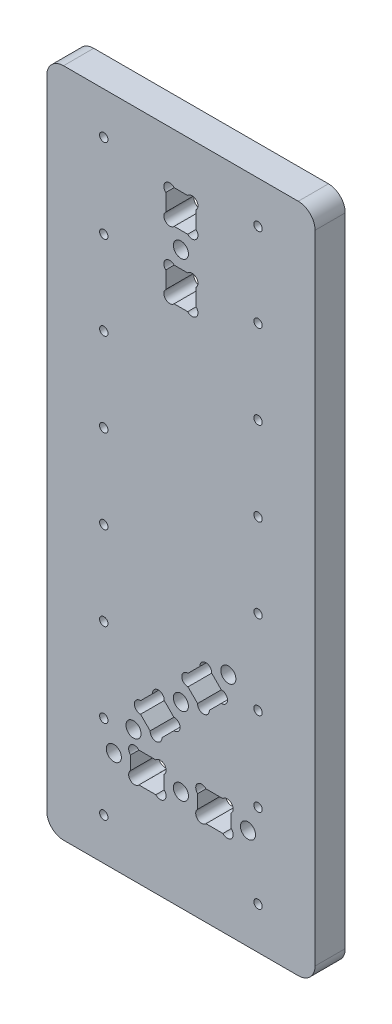
SolidWorks part; units mm, degrees
ref_plane "Plan de face" through (0, 0, 0) normal (0, 0, 1) x (1, 0, 0)
ref_plane "Plan de dessus" through (0, 0, 0) normal (0, 1, 0) x (1, 0, 0)
ref_plane "Plan de droite" through (0, 0, 0) normal (1, 0, 0) x (0, 0, -1)
sketch "Esquisse1" plane through (0, 0, 0) normal (0, 0, 1) x (1, 0, 0)
  line L1 (0, 0) -> (80, 0)
  line L2 (0, 0) -> (0, 200)
  line L3 (0, 200) -> (80, 200)
  line L4 (80, 0) -> (80, 200)
  dimension "D1" = 80
  dimension "D2" = 200
extrude "Boss.-Extru.1" add sketch "Esquisse1" along normal blind 9
sketch "Esquisse2" plane through (0, 0, 9) normal (0, 0, 1) x (1, 0, 0)
  line L0 (40, 0) -> (40, 200) construction
  line L1 (0, 0) -> (80, 0) construction
  line L2 (80, 200) -> (0, 200) construction
  line L3 (17, 0) -> (17, 200) construction
  line L4 (40, 100) -> (0, 100) construction
  line L5 (0, 200) -> (0, 0) construction
  circle A0 centre (17, 187.5) radius 1.25
  circle A1 centre (17, 87.5) radius 1.25
  circle A2 centre (17, 62.5) radius 1.25
  circle A3 centre (17, 37.5) radius 1.25
  circle A4 centre (17, 12.5) radius 1.25
  circle A5 centre (17, 162.5) radius 1.25
  circle A6 centre (17, 137.5) radius 1.25
  circle A7 centre (17, 112.5) radius 1.25
  circle A8 centre (63, 112.5) radius 1.25
  circle A9 centre (63, 137.5) radius 1.25
  circle A10 centre (63, 162.5) radius 1.25
  circle A11 centre (63, 12.5) radius 1.25
  circle A12 centre (63, 37.5) radius 1.25
  circle A13 centre (63, 62.5) radius 1.25
  circle A14 centre (63, 87.5) radius 1.25
  circle A15 centre (63, 187.5) radius 1.25
  dimension "D2" = 2.5
  dimension "D3" = 12.5
  dimension "D4" = 25
  dimension "D5" = 25
  dimension "D1" = 23
  dimension "D6" = 25
extrude "Enlèv. mat.-Extru.1" cut sketch "Esquisse2" against normal through all both and the other way through all
sketch "Esquisse3" plane through (0, 0, 9) normal (0, 0, 1) x (1, 0, 0)
  line L0 (43.182, 0) -> (43.182, 50) construction
  line L2 (43.182, 50) -> (46.7175, 53.5355) construction
  line L3 (46.7175, 53.5355) -> (53.7886, 60.6066)
  line L4 (53.7886, 60.6066) -> (47.4246, 66.9706)
  line L5 (47.4246, 66.9706) -> (40.3536, 59.8995)
  line L6 (40.3536, 59.8995) -> (46.7175, 53.5355)
  line L7 (43.182, 50) -> (32.8481, 60.3339) construction
  line L8 (33.2825, 52.8284) -> (39.6464, 46.4645)
  line L9 (26.2114, 45.7574) -> (33.2825, 52.8284)
  line L10 (32.5754, 39.3934) -> (26.2114, 45.7574)
  line L11 (39.6464, 46.4645) -> (32.5754, 39.3934)
  line L12 (26.2114, 45.7574) -> (17, 45.7574) construction
  line L13 (17, 45.7574) -> (17, 37.5) construction
  line L14 (53.7886, 60.6066) -> (63, 60.6066) construction
  line L15 (63, 60.6066) -> (63, 37.5) construction
  line L16 (0, 0) -> (80, 0) construction
  dimension "D1" = 135
  dimension "D2" = 9
  dimension "D3" = 10
  dimension "D4" = 5
  dimension "D5" = 50
extrude "Enlèv. mat.-Extru.2" cut sketch "Esquisse3" against normal through all both and the other way through all
fillet "Congé1" radius 5 4 edges at (0, 200, 4.5) (80, 200, 4.5) (80, 0, 4.5) (0, 0, 4.5)
sketch "Esquisse4" plane through (0, 0, 9) normal (0, 0, 1) x (1, 0, 0)
  line L0 (32.5754, 39.3934) -> (26.2114, 45.7574) construction
  line L1 (26.2114, 45.7574) -> (33.2825, 52.8284) construction
  line L2 (27.8641, 45.7574) -> (26.2114, 45.7574) construction
  line L3 (27.9614, 47.5074) -> (27.9614, 44.0074)
  line L4 (26.2114, 45.7574) -> (26.1114, 45.7574) construction
  line L5 (29.3934, 42.5754) -> (36.4645, 49.6464) construction
  line L6 (33.2825, 52.8284) -> (39.6464, 46.4645) construction
  line L7 (29.747, 49.2929) -> (36.1109, 42.9289) construction
  line L8 (39.6464, 46.4645) -> (32.5754, 39.3934) construction
  line L9 (33.2825, 52.8284) -> (33.2825, 52.9284) construction
  line L10 (33.2825, 51.1757) -> (33.2825, 52.8284) construction
  line L11 (31.5325, 51.0784) -> (35.0325, 51.0784)
  line L12 (37.9937, 46.4645) -> (39.6464, 46.4645) construction
  line L13 (39.6464, 46.4645) -> (39.7464, 46.4645) construction
  line L14 (32.5754, 39.3934) -> (32.5754, 39.2934) construction
  line L15 (32.5754, 41.0461) -> (32.5754, 39.3934) construction
  line L16 (37.8964, 44.7145) -> (37.8964, 48.2145)
  line L17 (34.3254, 41.1434) -> (30.8254, 41.1434)
  line L18 (36.4645, 49.6464) -> (43.5355, 56.7175) construction
  line L19 (46.7175, 53.5355) -> (40.3536, 59.8995) construction
  line L20 (40, 53.182) -> (41.6519, 51.5301) construction
  line L21 (52.1359, 60.6066) -> (53.7886, 60.6066) construction
  line L22 (53.7886, 60.6066) -> (53.8886, 60.6066) construction
  line L23 (46.7175, 53.5355) -> (46.7175, 53.4355) construction
  line L24 (46.7175, 55.1882) -> (46.7175, 53.5355) construction
  line L25 (42.0063, 59.8995) -> (40.3536, 59.8995) construction
  line L26 (40.3536, 59.8995) -> (40.2536, 59.8995) construction
  line L27 (43.8891, 63.435) -> (50.253, 57.0711) construction
  line L28 (50.6066, 63.7886) -> (43.5355, 56.7175) construction
  line L29 (47.4246, 66.9706) -> (47.4246, 67.0706) construction
  line L30 (47.4246, 65.3179) -> (47.4246, 66.9706) construction
  line L31 (52.0386, 58.8566) -> (52.0386, 62.3566)
  line L32 (48.4675, 55.2855) -> (44.9675, 55.2855)
  line L33 (42.1036, 61.6495) -> (42.1036, 58.1495)
  line L34 (45.6746, 65.2206) -> (49.1746, 65.2206)
  line L35 (29.3934, 42.5754) -> (25.8579, 39.0398) construction
  arc A0 (27.9614, 44.0074) -> (27.9614, 47.5074) centre (27.8641, 45.7574) cw
  arc A1 (35.0325, 51.0784) -> (31.5325, 51.0784) centre (33.2825, 51.1757) ccw
  arc A2 (37.8964, 48.2145) -> (37.8964, 44.7145) centre (37.9937, 46.4645) cw
  arc A3 (30.8254, 41.1434) -> (34.3254, 41.1434) centre (32.5754, 41.0461) ccw
  arc A4 (52.0386, 62.3566) -> (52.0386, 58.8566) centre (52.1359, 60.6066) cw
  arc A5 (44.9675, 55.2855) -> (48.4675, 55.2855) centre (46.7175, 55.1882) ccw
  arc A6 (42.1036, 58.1495) -> (42.1036, 61.6495) centre (42.0063, 59.8995) cw
  arc A7 (49.1746, 65.2206) -> (45.6746, 65.2206) centre (47.4246, 65.3179) ccw
  circle A8 centre (40, 53.182) radius 2.25
  circle A9 centre (25.8579, 39.0398) radius 2.25
  circle A10 centre (54.1421, 67.3241) radius 2.25
  dimension "D2" = 3.5
  dimension "D3" = 5
  dimension "D4" = 4.5
  dimension "D1" = 0.1
extrude "Enlèv. mat.-Extru.3" cut sketch "Esquisse4" against normal through all both and the other way through all
sketch "Esquisse5" plane through (0, 0, 9) normal (0, 0, 1) x (1, 0, 0)
  line L0 (52.0386, 58.8566) -> (48.4675, 55.2855) construction
  line L1 (49.1746, 65.2206) -> (52.0386, 62.3566) construction
  line L2 (42.1036, 61.6495) -> (45.6746, 65.2206) construction
  line L3 (44.9675, 55.2855) -> (42.1036, 58.1495) construction
  line L4 (37.8964, 44.7145) -> (34.3254, 41.1434) construction
  line L5 (35.0325, 51.0784) -> (37.8964, 48.2145) construction
  line L6 (27.9614, 47.5074) -> (31.5325, 51.0784) construction
  line L7 (30.8254, 41.1434) -> (27.9614, 44.0074) construction
  line L8 (52.0386, 58.8566) -> (48.4675, 55.2855) construction
  line L9 (49.1746, 65.2206) -> (52.0386, 62.3566) construction
  line L10 (42.1036, 61.6495) -> (45.6746, 65.2206) construction
  line L11 (44.9675, 55.2855) -> (42.1036, 58.1495) construction
  line L12 (37.8964, 44.7145) -> (34.3254, 41.1434) construction
  line L13 (35.0325, 51.0784) -> (37.8964, 48.2145) construction
  line L14 (27.9614, 47.5074) -> (31.5325, 51.0784) construction
  line L15 (30.8254, 41.1434) -> (27.9614, 44.0074) construction
  line L16 (54.1421, 67.3241) -> (40, 53.182) construction
  line L17 (54.1421, 67.3241) -> (12.0169, 41.591) construction
  line L18 (52.5251, 25.5) -> (47.4749, 25.5)
  line L19 (55, 32.0251) -> (55, 27.9749)
  line L20 (47.4749, 34.5) -> (52.5251, 34.5)
  line L21 (45, 27.9749) -> (45, 32.0251)
  line L22 (32.5251, 25.5) -> (27.4749, 25.5)
  line L23 (35, 32.0251) -> (35, 27.9749)
  line L24 (27.4749, 34.5) -> (32.5251, 34.5)
  line L25 (25, 27.9749) -> (25, 32.0251)
  line L26 (60, 30) -> (40, 30) construction
  line L27 (40, 30) -> (40, 0) construction
  line L28 (44.5, 182.5251) -> (44.5, 177.4749)
  line L29 (5, 0) -> (75, 0) construction
  line L30 (37.9749, 185) -> (42.0251, 185)
  line L31 (35.5, 177.4749) -> (35.5, 182.5251)
  line L32 (42.0251, 175) -> (37.9749, 175)
  line L33 (44.5, 162.5251) -> (44.5, 157.4749)
  line L34 (37.9749, 165) -> (42.0251, 165)
  line L35 (35.5, 157.4749) -> (35.5, 162.5251)
  line L36 (42.0251, 155) -> (37.9749, 155)
  line L37 (40, 190) -> (40, 170) construction
  line L38 (75, 200) -> (5, 200) construction
  circle A0 centre (54.1421, 67.3241) radius 2.25 construction
  arc A1 (52.0386, 58.8566) -> (52.0386, 62.3566) centre (52.1359, 60.6066) ccw construction
  arc A2 (49.1746, 65.2206) -> (45.6746, 65.2206) centre (47.4246, 65.3179) ccw construction
  arc A3 (42.1036, 61.6495) -> (42.1036, 58.1495) centre (42.0063, 59.8995) ccw construction
  arc A4 (44.9675, 55.2855) -> (48.4675, 55.2855) centre (46.7175, 55.1882) ccw construction
  circle A5 centre (40, 53.182) radius 2.25 construction
  circle A6 centre (25.8579, 39.0398) radius 2.25 construction
  arc A7 (30.8254, 41.1434) -> (34.3254, 41.1434) centre (32.5754, 41.0461) ccw construction
  arc A8 (37.8964, 44.7145) -> (37.8964, 48.2145) centre (37.9937, 46.4645) ccw construction
  arc A9 (35.0325, 51.0784) -> (31.5325, 51.0784) centre (33.2825, 51.1757) ccw construction
  arc A10 (27.9614, 47.5074) -> (27.9614, 44.0074) centre (27.8641, 45.7574) ccw construction
  circle A11 centre (54.1421, 67.3241) radius 2.25 construction
  arc A12 (52.0386, 58.8566) -> (52.0386, 62.3566) centre (52.1359, 60.6066) ccw construction
  arc A13 (49.1746, 65.2206) -> (45.6746, 65.2206) centre (47.4246, 65.3179) ccw construction
  arc A14 (42.1036, 61.6495) -> (42.1036, 58.1495) centre (42.0063, 59.8995) ccw construction
  arc A15 (44.9675, 55.2855) -> (48.4675, 55.2855) centre (46.7175, 55.1882) ccw construction
  circle A16 centre (40, 53.182) radius 2.25 construction
  circle A17 centre (25.8579, 39.0398) radius 2.25 construction
  arc A18 (30.8254, 41.1434) -> (34.3254, 41.1434) centre (32.5754, 41.0461) ccw construction
  arc A19 (37.8964, 44.7145) -> (37.8964, 48.2145) centre (37.9937, 46.4645) ccw construction
  arc A20 (35.0325, 51.0784) -> (31.5325, 51.0784) centre (33.2825, 51.1757) ccw construction
  arc A21 (27.9614, 47.5074) -> (27.9614, 44.0074) centre (27.8641, 45.7574) ccw construction
  circle A22 centre (60, 30) radius 2.25
  arc A23 (52.5251, 25.5) -> (55, 27.9749) centre (53.8314, 26.6686) ccw
  arc A24 (55, 32.0251) -> (52.5251, 34.5) centre (53.8314, 33.3314) ccw
  arc A25 (47.4749, 34.5) -> (45, 32.0251) centre (46.1686, 33.3314) ccw
  arc A26 (45, 27.9749) -> (47.4749, 25.5) centre (46.1686, 26.6686) ccw
  circle A27 centre (40, 30) radius 2.25
  circle A28 centre (20, 30) radius 2.25
  arc A29 (25, 27.9749) -> (27.4749, 25.5) centre (26.1686, 26.6686) ccw
  arc A30 (32.5251, 25.5) -> (35, 27.9749) centre (33.8314, 26.6686) ccw
  arc A31 (35, 32.0251) -> (32.5251, 34.5) centre (33.8314, 33.3314) ccw
  arc A32 (27.4749, 34.5) -> (25, 32.0251) centre (26.1686, 33.3314) ccw
  arc A34 (44.5, 182.5251) -> (42.0251, 185) centre (43.3314, 183.8314) ccw
  arc A35 (37.9749, 185) -> (35.5, 182.5251) centre (36.6686, 183.8314) ccw
  arc A36 (35.5, 177.4749) -> (37.9749, 175) centre (36.6686, 176.1686) ccw
  arc A37 (42.0251, 175) -> (44.5, 177.4749) centre (43.3314, 176.1686) ccw
  circle A38 centre (40, 170) radius 2.25
  arc A40 (42.0251, 155) -> (44.5, 157.4749) centre (43.3314, 156.1686) ccw
  arc A41 (44.5, 162.5251) -> (42.0251, 165) centre (43.3314, 163.8314) ccw
  arc A42 (37.9749, 165) -> (35.5, 162.5251) centre (36.6686, 163.8314) ccw
  arc A43 (35.5, 157.4749) -> (37.9749, 155) centre (36.6686, 156.1686) ccw
  circle A44 centre (40, 150) radius 2.25 [skipped]
  circle A45 centre (40, 190) radius 2.25 [skipped]
  point P33 (-95.9274, 30)
  point P66 (12.0169, 41.591)
  point P101 (-30, 100)
  dimension "D1" = 30
  dimension "D3" = 45
  dimension "D5" = 30
  dimension "D2" = 2
  dimension "D4" = 2
extrude "Enlèv. mat.-Extru.4" cut sketch "Esquisse5" against normal through all both and the other way through all
